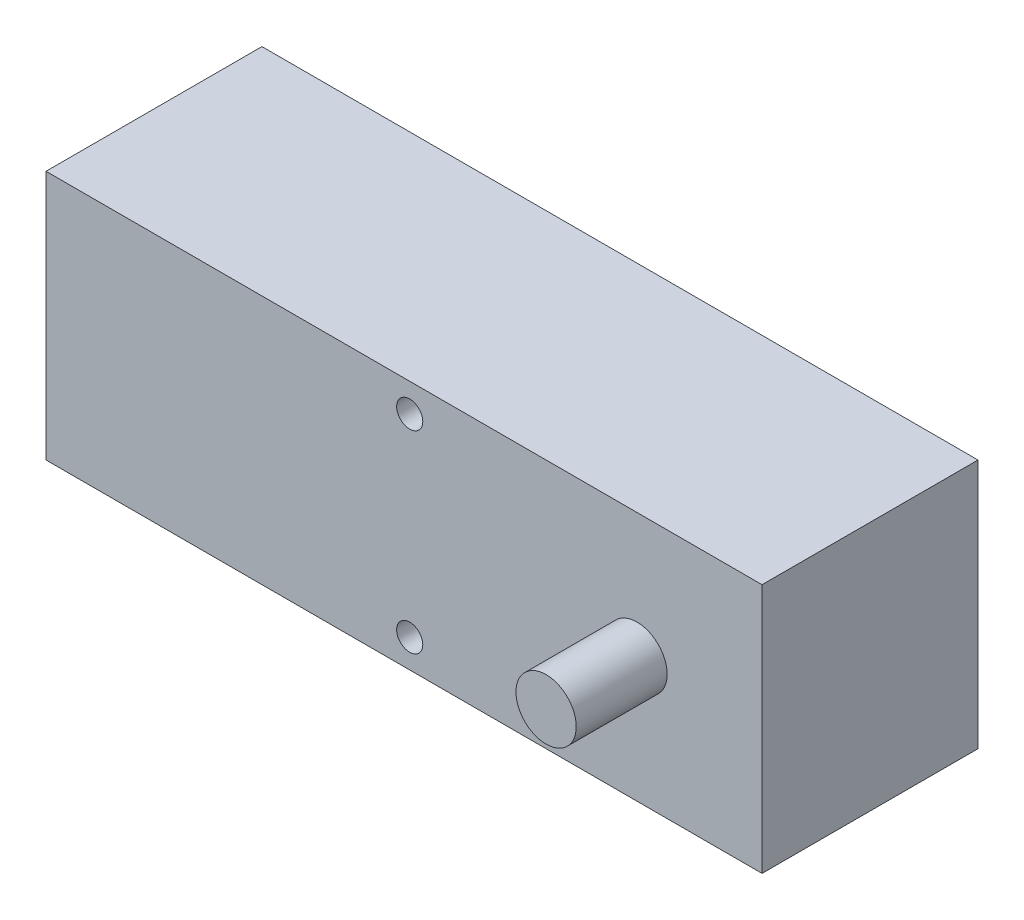
SolidWorks part; units mm, degrees
ref_plane "Front Plane" through (0, 0, 0) normal (0, 0, 1) x (1, 0, 0)
ref_plane "Top Plane" through (0, 0, 0) normal (0, 1, 0) x (1, 0, 0)
ref_plane "Right Plane" through (0, 0, 0) normal (1, 0, 0) x (0, 0, -1)
sketch "Sketch1" plane through (0, 0, 0) normal (0, 0, 1) x (1, 0, 0)
  line L0 (32, 19.5) -> (32, 2.5) construction
  line L1 (0, 0) -> (63, 0)
  line L2 (0, 0) -> (0, 22)
  line L3 (0, 22) -> (63, 22)
  line L4 (63, 0) -> (63, 22)
  circle A0 centre (32, 19.5) radius 1.15
  circle A1 centre (32, 2.5) radius 1.15
  point P9 (32, 11)
  point P10 (0, 11)
  dimension "D4" = 2.3
  dimension "D1" = 63
  dimension "D2" = 22
  dimension "D3" = 17
  dimension "D5" = 31
extrude "Boss-Extrude1" add sketch "Sketch1" along normal blind 19
sketch "Sketch2" plane through (0, 0, 19) normal (0, 0, 1) x (1, 0, 0)
  line L0 (63, 0) -> (63, 22) construction
  circle A0 centre (52, 11) radius 2.65
  point P2 (0, 0)
  point P5 (63, 11)
  dimension "D2" = 5.3
  dimension "D1" = 11
extrude "Boss-Extrude2" add sketch "Sketch2" along normal blind 8
